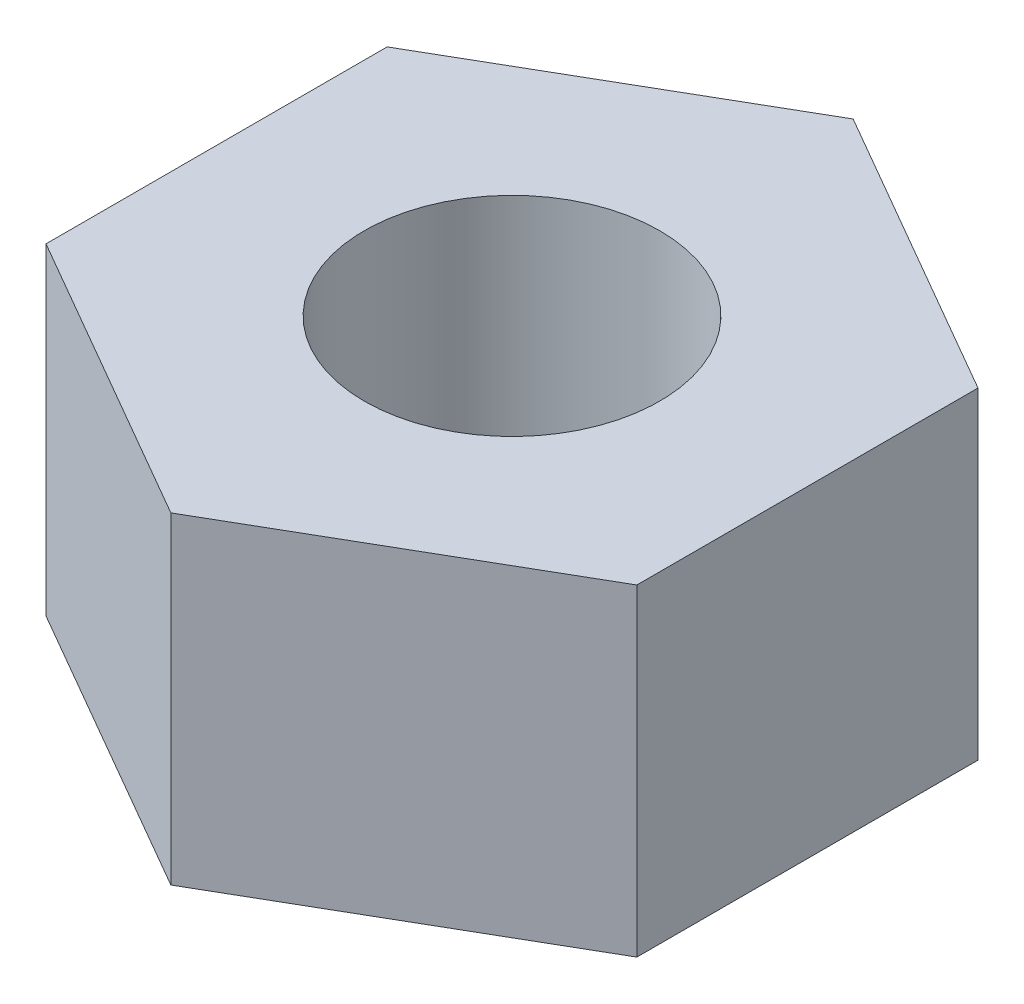
SolidWorks part; units mm, degrees
ref_plane "Front Plane" through (0, 0, 0) normal (0, 0, 1) x (1, 0, 0)
ref_plane "Top Plane" through (0, 0, 0) normal (0, 1, 0) x (1, 0, 0)
ref_plane "Right Plane" through (0, 0, 0) normal (1, 0, 0) x (0, 0, -1)
sketch "Sketch1" plane through (0, 0, 0) normal (0, 1, 0) x (1, 0, 0)
  line L1 (0, 3.1754) -> (-2.75, 1.5877)
  line L2 (-2.75, 1.5877) -> (-2.75, -1.5877)
  line L3 (-2.75, -1.5877) -> (0, -3.1754)
  line L4 (0, -3.1754) -> (2.75, -1.5877)
  line L5 (2.75, -1.5877) -> (2.75, 1.5877)
  line L6 (2.75, 1.5877) -> (0, 3.1754)
  circle A0 centre (0, 0) radius 2.75 construction
  circle A1 centre (0, 0) radius 1.375
  dimension "D1" = 5.5
  dimension "D2" = 2.75
extrude "Boss-Extrude1" add sketch "Sketch1" along normal blind 3
